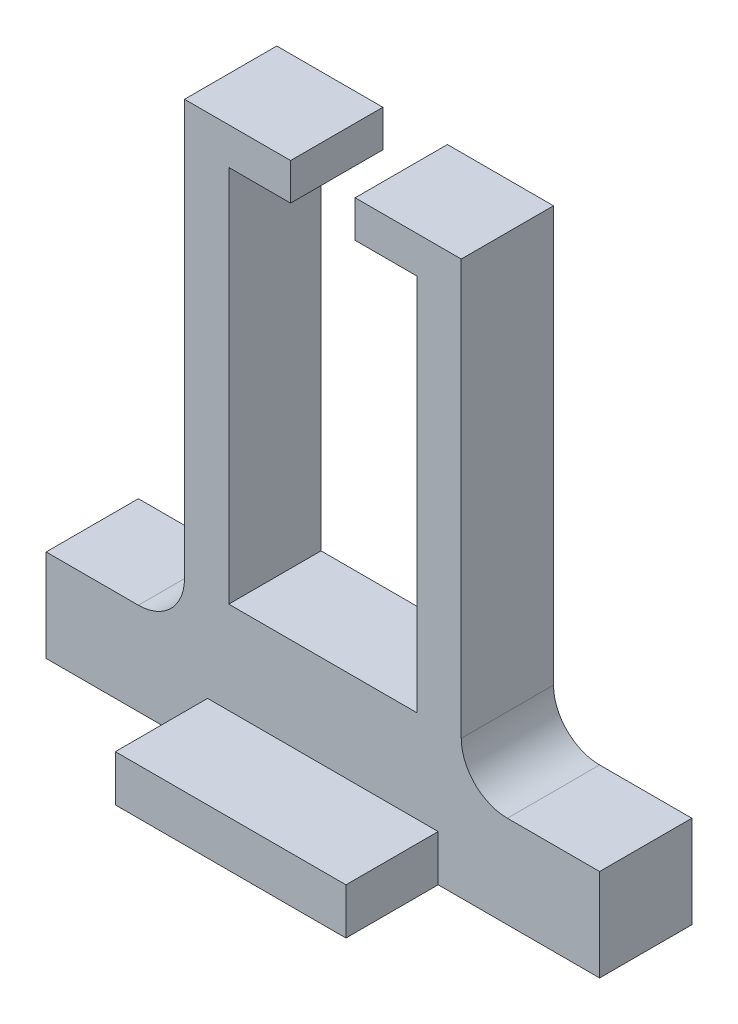
SolidWorks part; units mm, degrees
ref_plane "Front Plane" through (0, 0, 0) normal (0, 0, 1) x (1, 0, 0)
ref_plane "Top Plane" through (0, 0, 0) normal (0, 1, 0) x (1, 0, 0)
ref_plane "Right Plane" through (0, 0, 0) normal (1, 0, 0) x (0, 0, -1)
sketch "Sketch1" plane through (0, 0, 0) normal (0, 0, 1) x (1, 0, 0)
  line L0 (-15, 24.5) -> (-15, -20.5)
  line L1 (-10.2, 20.5) -> (10.2, 20.5)
  line L2 (-10.2, 20.5) -> (-10.2, -20.5)
  line L3 (-10.2, -20.5) -> (10.2, -20.5)
  line L4 (10.2, 20.5) -> (10.2, -20.5)
  line L5 (-10.2, 20.5) -> (10.2, -20.5) construction
  line L6 (-10.2, -20.5) -> (10.2, 20.5) construction
  line L7 (-15, 24.5) -> (15, 24.5)
  line L11 (15, 24.5) -> (15, -20.5)
  line L12 (20, -25.5) -> (30, -25.5)
  line L13 (30, -25.5) -> (30, -35.5)
  line L14 (30, -35.5) -> (-30, -35.5)
  line L15 (-30, -35.5) -> (-30, -25.5)
  line L16 (-30, -25.5) -> (-20, -25.5)
  arc A2 (-15, -20.5) -> (-20, -25.5) centre (-20, -20.5) cw
  arc A3 (20, -25.5) -> (15, -20.5) centre (20, -20.5) cw
  point P0 (0, 0)
  point P6 (0, 10.5)
  point P9 (0, 0)
  point P10 (30, -30.5)
  point P19 (0, 24.5)
  point P29 (15, -25.5)
  dimension "D14" = 5
  dimension "D1" = 20.4
  dimension "D2" = 41
  dimension "D3" = 31
  dimension "D5" = 15
  dimension "D6" = 4
  dimension "D7" = 30
  dimension "D8" = 50
  dimension "D9" = 10
extrude "Boss-Extrude1" add sketch "Sketch1" along normal blind 10
sketch "Sketch2" plane through (0, 24.5, 0) normal (0, 1, 0) x (1, 0, 0)
  line L0 (-3.5, 0) -> (-3.5, -10)
  line L1 (15, 0) -> (-15, 0) construction
  line L2 (15, -10) -> (-15, -10) construction
  line L3 (-3.5, -10) -> (3.5, -10)
  line L4 (3.5, -10) -> (3.5, 0)
  line L5 (3.5, 0) -> (-3.5, 0)
  dimension "D1" = 3.5
  dimension "D2" = 3.5
extrude "Cut-Extrude1" cut sketch "Sketch2" against normal up to next
sketch "Sketch3" plane through (0, 0, 10) normal (0, 0, 1) x (1, 0, 0)
  line L5 (-30, -35.5) -> (30, -35.5) construction
  line L6 (-12.5, -35.5) -> (12.5, -35.5)
  line L7 (-12.5, -35.5) -> (-12.5, -30.5)
  line L8 (-12.5, -30.5) -> (12.5, -30.5)
  line L9 (12.5, -35.5) -> (12.5, -30.5)
  line L10 (0, 0) -> (0, -67.0129) construction
  dimension "D1" = 25
  dimension "D2" = 5
extrude "Boss-Extrude2" add sketch "Sketch3" along normal blind 10
